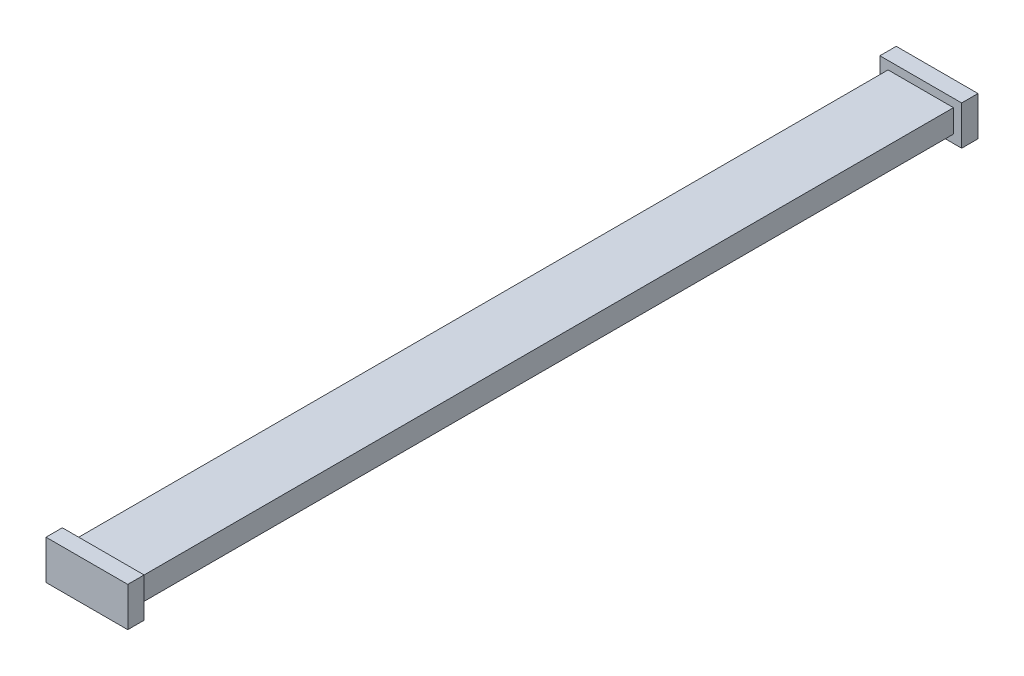
SolidWorks part; units mm, degrees
ref_plane "前视基准面" through (0, 0, 0) normal (0, 0, 1) x (1, 0, 0)
ref_plane "上视基准面" through (0, 0, 0) normal (0, 1, 0) x (1, 0, 0)
ref_plane "右视基准面" through (0, 0, 0) normal (1, 0, 0) x (0, 0, -1)
sketch "草图1" plane through (0, 0, 0) normal (0, 0, 1) x (1, 0, 0)
  line L1 (-10, 3.5) -> (10, 3.5)
  line L2 (-10, 3.5) -> (-10, -3.5)
  line L3 (-10, -3.5) -> (10, -3.5)
  line L4 (10, 3.5) -> (10, -3.5)
  line L5 (-10, 3.5) -> (10, -3.5) construction
  line L6 (-10, -3.5) -> (10, 3.5) construction
  point P0 (0, 0)
  dimension "D1" = 20
  dimension "D2" = 7
extrude "凸台-拉伸1" add sketch "草图1" along normal blind 250
sketch "草图2" plane through (0, 0, 250) normal (0, 0, 1) x (1, 0, 0)
  line L1 (12.5, -6) -> (-12.5, -6)
  line L2 (12.5, -6) -> (12.5, 6)
  line L3 (12.5, 6) -> (-12.5, 6)
  line L4 (-12.5, -6) -> (-12.5, 6)
  line L5 (12.5, -6) -> (-12.5, 6) construction
  line L6 (12.5, 6) -> (-12.5, -6) construction
  point P0 (0, 0)
  dimension "D1" = 25
  dimension "D2" = 12
extrude "凸台-拉伸2" add sketch "草图2" along normal blind 5
sketch "草图3" plane through (0, 0, 0) normal (0, 0, -1) x (-1, 0, 0)
  line L4 (12.5, -6) -> (12.5, 6)
  line L5 (12.5, 6) -> (-12.5, 6)
  line L6 (-12.5, 6) -> (-12.5, -6)
  line L7 (-12.5, -6) -> (12.5, -6)
  line L8 (12.5, -6) -> (12.5, 6)
  line L9 (12.5, 6) -> (-12.5, 6)
  line L10 (-12.5, 6) -> (-12.5, -6)
  line L11 (-12.5, -6) -> (12.5, -6)
  dimension "D1" = 0
extrude "凸台-拉伸3" add sketch "草图3" along normal blind 5
